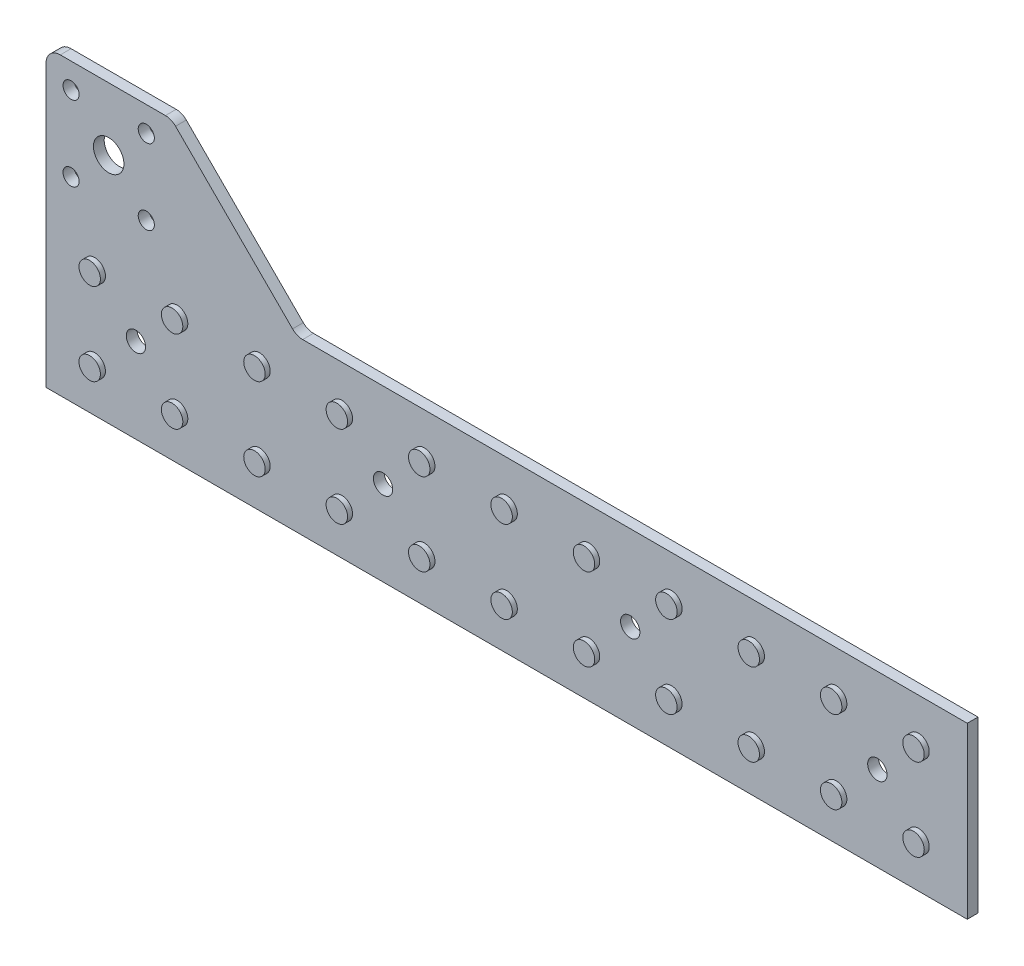
SolidWorks part; units mm, degrees
ref_plane "Front Plane" through (0, 0, 0) normal (0, 0, 1) x (1, 0, 0)
ref_plane "Top Plane" through (0, 0, 0) normal (0, 1, 0) x (1, 0, 0)
ref_plane "Right Plane" through (0, 0, 0) normal (1, 0, 0) x (0, 0, -1)
sketch "Sketch1" plane through (0, 0, 0) normal (0, 0, 1) x (1, 0, 0)
  line L1 (0, 0) -> (257.2, 0)
  line L2 (0, 0) -> (0, 47.4)
  line L3 (70, 47.4) -> (257.2, 47.4)
  line L17 (0, 23.7) -> (257.2, 23.7) construction
  line L18 (257.2, 47.4) -> (257.2, 0)
  line L19 (35, 82.4) -> (70, 47.4)
  line L20 (0, 47.4) -> (0, 82.4)
  line L21 (0, 82.4) -> (35, 82.4)
  circle A0 centre (232.1, 23.7) radius 2.7
  circle A1 centre (163.1, 23.7) radius 2.7
  circle A2 centre (94.1, 23.7) radius 2.7
  circle A3 centre (25.1, 23.7) radius 2.7
  point P19 (0, 23.7)
  point P26 (257.2, 47.4)
  dimension "D1" = 5.4
  dimension "D2" = 35
  dimension "D6" = 45
  dimension "D3" = 35
  dimension "D4" = 47.4
  dimension "D5" = 257.2
  dimension "D7" = 47.4
  dimension "D9" = 25.1
  dimension "D10" = 69
  dimension "D11" = 69
  dimension "D12" = 69
extrude "Boss-Extrude1" add sketch "Sketch1" along normal blind 3
ref_plane "Plane2" through (0, 23.7, 0) normal (0, -1, 0) x (-1, 0, 0)
sketch "Sketch3" plane through (0, 0, 3) normal (0, 0, 1) x (1, 0, 0)
  line L0 (0, 82.4) -> (0, 0) construction
  line L1 (0, 0) -> (257.2, 0) construction
  circle A0 centre (13.6, 12.2) radius 2.995
  dimension "D3" = 5.99
  dimension "D1" = 13.6
  dimension "D2" = 12.2
extrude "Boss-Extrude2" add sketch "Sketch3" along normal blind 1.4
pattern_linear "LPattern1" count 2 spacing 23 along (0, 1, 0) count 11 spacing 23 along (1, 0, 0) of "Boss-Extrude2"
fillet "Fillet2" radius 4 3 edges at (0, 82.4, 1.5) (35, 82.4, 1.5) (70, 47.4, 1.5)
sketch "Sketch5" plane through (0, 0, 3) normal (0, 0, 1) x (1, 0, 0)
  line L0 (28, 75.4) -> (7, 54.4) construction
  line L1 (7, 75.4) -> (28, 54.4) construction
  line L3 (0, 78.4) -> (0, 0) construction
  line L4 (33.3431, 82.4) -> (4, 82.4) construction
  circle A0 centre (17.5, 64.9) radius 4.25
  circle A1 centre (7, 75.4) radius 2.25
  circle A2 centre (28, 75.4) radius 2.25
  circle A3 centre (28, 54.4) radius 2.25
  circle A4 centre (7, 54.4) radius 2.25
  point P11 (15.5, 56.9)
  point P12 (15.5, 56.9)
  dimension "D1" = 4.5
  dimension "D4" = 8.5
  dimension "D5" = 17.5
  dimension "D2" = 21
  dimension "D3" = 21
  dimension "D6" = 17.5
extrude "Cut-Extrude2" cut sketch "Sketch5" against normal through all
